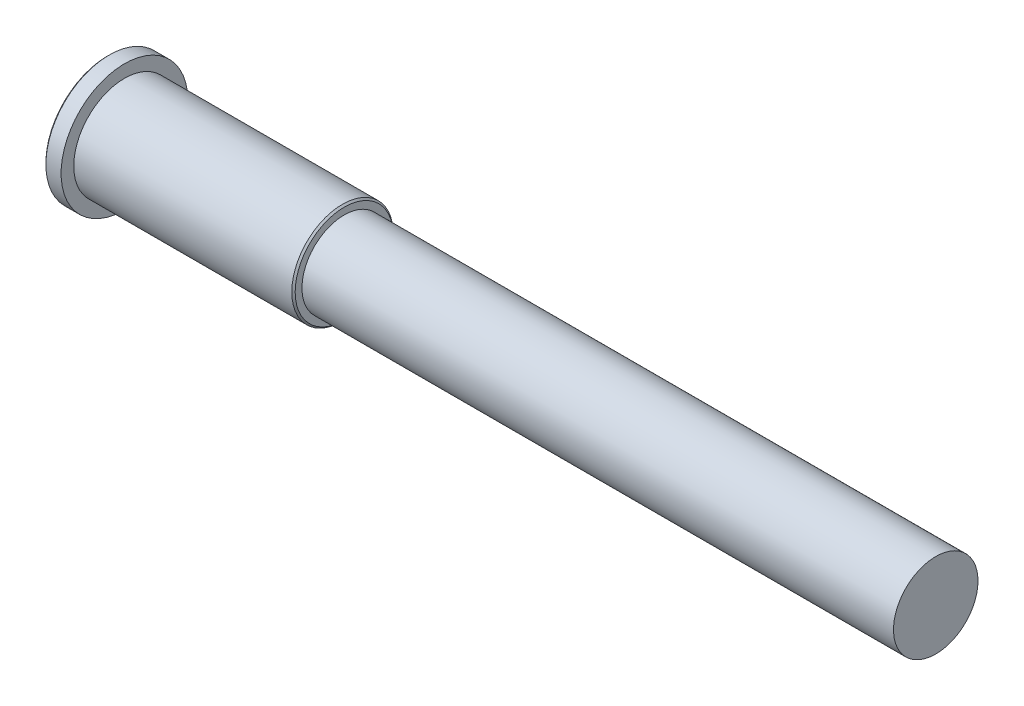
SolidWorks part; units mm, degrees
ref_plane "Front Plane" through (0, 0, 0) normal (0, 0, 1) x (1, 0, 0)
ref_plane "Top Plane" through (0, 0, 0) normal (0, 1, 0) x (1, 0, 0)
ref_plane "Right Plane" through (0, 0, 0) normal (1, 0, 0) x (0, 0, -1)
sketch "Sketch1" plane through (0, 0, 0) normal (1, 0, 0) x (0, 0, -1)
  circle A0 centre (0, 0) radius 7.5
  dimension "D1" = 15
extrude "Boss-Extrude1" add sketch "Sketch1" along normal blind 2
sketch "Sketch2" plane through (2, 0, 0) normal (1, 0, 0) x (0, 0, -1)
  circle A0 centre (0, 0) radius 6
  dimension "D1" = 12
extrude "Boss-Extrude2" add sketch "Sketch2" along normal blind 26
sketch "Sketch3" plane through (28, 0, 0) normal (1, 0, 0) x (0, 0, -1)
  circle A0 centre (0, 0) radius 5
  dimension "D1" = 10
extrude "Boss-Extrude3" add sketch "Sketch3" along normal blind 70
chamfer "Chamfer1" distance 0.2 angle 45 2 edges at (0, 0, -7.5) (28, 0, -6)
scale "Scale1" scale about centroid uniform scaling yes scale factor 0.317565
